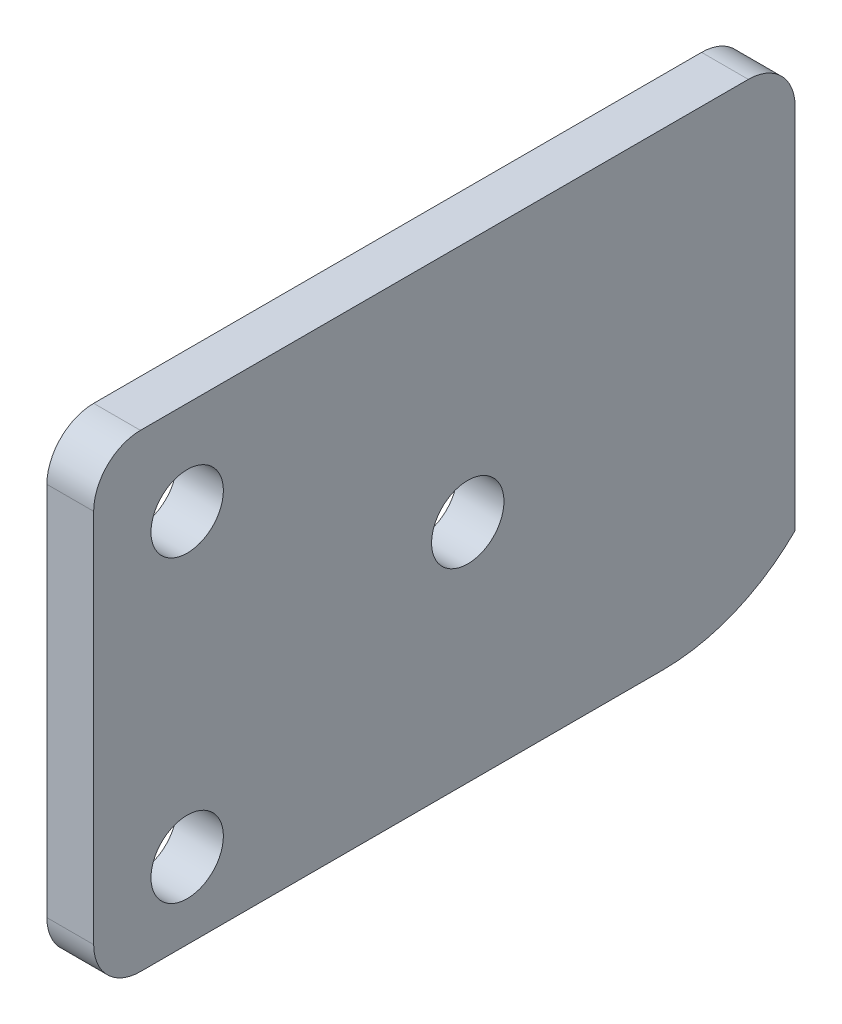
SolidWorks part; units mm, degrees
material "AISI 4340 Steel, annealed"
ref_plane "X-Y Datum" through (0, 0, 0) normal (0, 0, 1) x (1, 0, 0)
ref_plane "X-Z Datum" through (0, 0, 0) normal (0, 1, 0) x (1, 0, 0)
ref_plane "Y-Z Datum" through (0, 0, 0) normal (1, 0, 0) x (0, 0, -1)
sketch "Sketch1" plane through (0, 0, 0) normal (1, 0, 0) x (0, 0, -1)
  line L0 (2.961, -20.7167) -> (-30.7, -20.7167) construction
  line L1 (-25.4, 11.1125) -> (22.225, 11.1125)
  line L2 (-25.4, 11.1125) -> (-25.4, -20.7167)
  line L3 (-25.4, -20.7167) -> (13.2578, -20.7167)
  line L4 (22.225, 11.1125) -> (22.225, -17.01)
  arc A0 (20.6815, -18.321) -> (23.8637, -15.0027) centre (13.2578, -8.0167) ccw construction
  arc A1 (19.5141, -19.0688) -> (20.6815, -18.321) centre (13.2578, -8.0167) ccw construction
  arc A2 (13.2578, -20.7167) -> (19.5141, -19.0688) centre (13.2578, -8.0167) ccw construction
  arc A3 (20.6815, -18.321) -> (22.225, -17.01) centre (13.2578, -8.0167) ccw
  arc A4 (19.5141, -19.0688) -> (20.6815, -18.321) centre (13.2578, -8.0167) ccw
  arc A5 (13.2578, -20.7167) -> (19.5141, -19.0688) centre (13.2578, -8.0167) ccw
  point P0 (0, 0)
  dimension "D1" = 6.35
  dimension "D2" = 6.35
  dimension "D3" = 9.525
extrude "Boss-Extrude1" add sketch "Sketch1" along normal blind 3.175
sketch "Sketch4" plane through (0, 0, 0) normal (-1, 0, 0) x (0, 0, 1)
  point P0 (19.05, 4.7625)
  point P1 (-15.875, -5.3975)
  point P2 (19.05, -15.5575)
  dimension "D1" = 20.32
  dimension "D2" = 15.5575
  dimension "D3" = 19.05
  dimension "D4" = 15.875
  dimension "D5" = 10.16
hole_wizard "#10 (0.1935) Diameter Hole1" positions "Sketch5" profile "Sketch6" hole size "#10" standard "ANSI Inch"
sketch "Sketch5" plane through (0, 0, 0) normal (-1, 0, 0) x (0, 0, 1)
  point P0 (19.05, 4.7625)
  point P3 (19.05, -15.5575)
  point P6 (0, -5.3975)
  point P9 (0, 0)
  point P10 (0, 0)
  point P12 (0, 0)
  point P13 (0, 0)
  point P14 (0, 0)
  point P15 (0, 0)
  dimension "D1" = 19.05
  dimension "D2" = 15.5575
  dimension "D3" = 4.7625
  dimension "D4" = 19.05
  dimension "D5" = 10.16
sketch "Sketch6" plane through (0, 4.7625, 19.05) normal (0, 1, 0) x (0, 0, 1)
  line L0 (0, 0) -> (0, 11.176)
  line L1 (0, 11.176) -> (2.4574, 9.6994)
  line L2 (2.4574, 9.6994) -> (2.4574, 0)
  line L5 (2.4574, 0) -> (0, 0)
  line L10 (0, 11.176) -> (-2.4575, 9.6994) construction
  line L11 (0, -6.35) -> (0, 107.95) construction
  dimension "Hole Dia." = 4.9149
  dimension "Hole Depth" = 11.176
  dimension "Drill Angle" = 118
fillet "Fillet1" radius 3.175 3 edges at (1.5875, 11.1125, -22.225) (1.5875, 11.1125, 25.4) (1.5875, -20.7167, 25.4)
